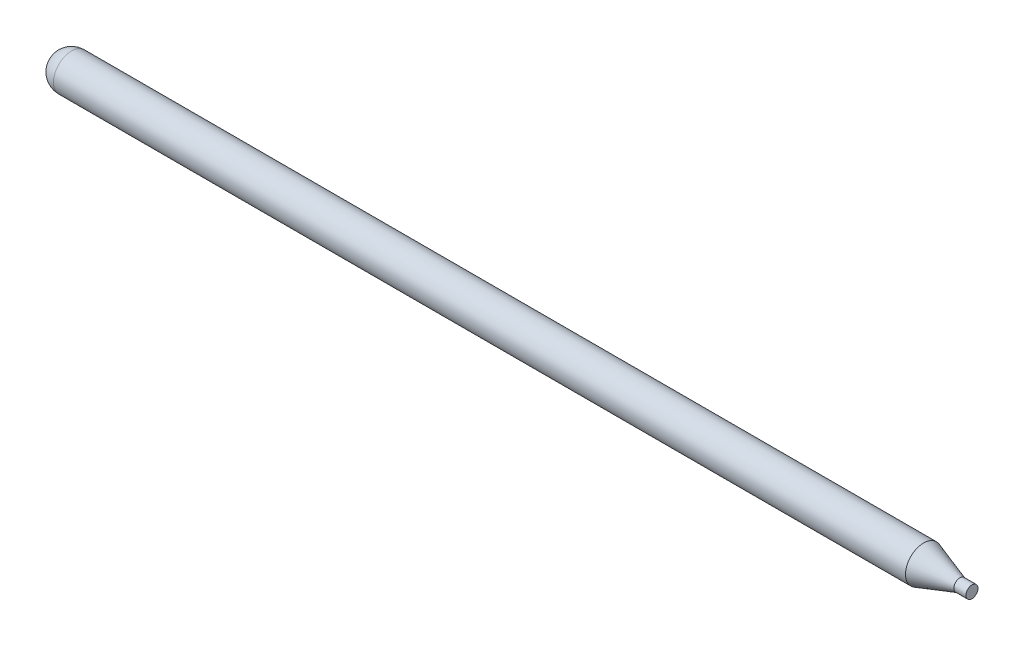
SolidWorks part; units mm, degrees
ref_plane "Alzado" through (0, 0, 0) normal (0, 0, 1) x (1, 0, 0)
ref_plane "Planta" through (0, 0, 0) normal (0, 1, 0) x (1, 0, 0)
ref_plane "Vista lateral" through (0, 0, 0) normal (1, 0, 0) x (0, 0, -1)
sketch "Croquis1" plane through (0, 0, 0) normal (0, 0, 1) x (1, 0, 0)
  line L0 (72, 3) -> (78, 1)
  line L1 (-69, 3) -> (72, 3)
  line L3 (-72, 0) -> (72, 0)
  line L5 (78, 1) -> (80, 1)
  line L7 (78, 0) -> (80, 0)
  line L8 (80, 1) -> (80, 0)
  line L9 (72, 0) -> (78, 0)
  arc A0 (-69, 3) -> (-72, 0) centre (-69, 0) ccw
  point P6 (26.5685, 0.3251)
  point P7 (0, 0)
  point P8 (0, 0)
  point P12 (22.5822, 0.4332)
  point P13 (0, 0)
  point P14 (16.7304, 3.3063)
  point P15 (0, 0)
  point P16 (0, 0)
  point P17 (0, 0)
  point P18 (0, 0)
  point P19 (139.0013, -0.3443)
  point P20 (149.8306, 4.3917)
  point P21 (0, 0)
  dimension "D1" = 3
  dimension "D2" = 150
  dimension "D3" = 6
  dimension "D4" = 2
  dimension "D5" = 3
  dimension "D6" = 1
revolve "Revolución3" add sketch "Croquis1" angle 360 about L3
